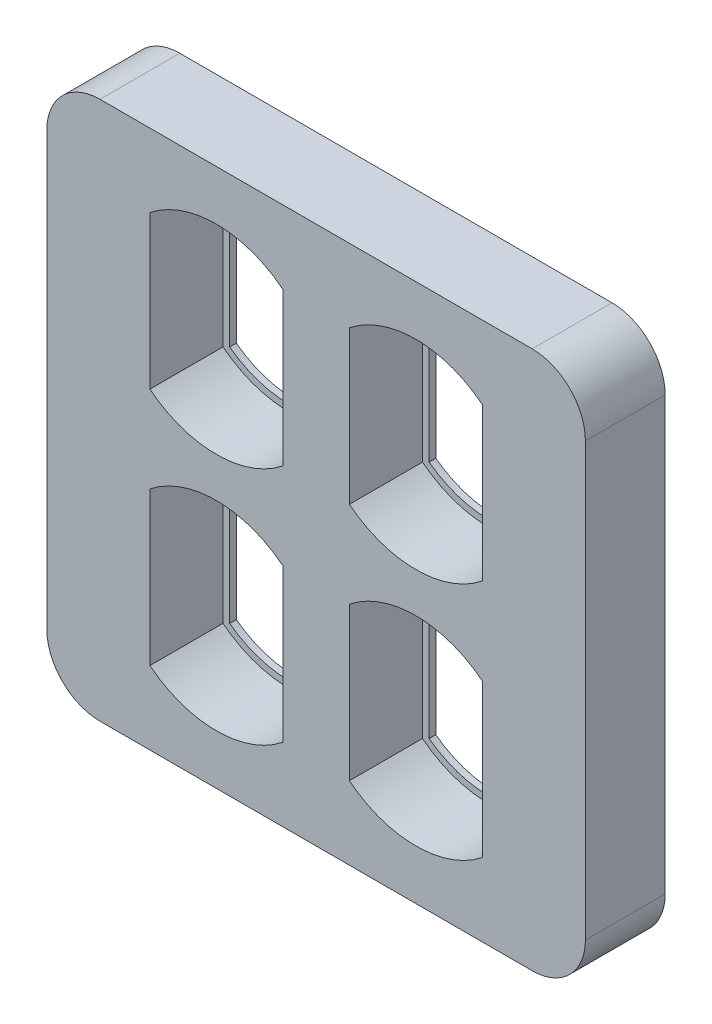
SolidWorks part; units mm, degrees
material "ABS-White"
ref_plane "Front Plane" through (0, 0, 0) normal (0, 0, 1) x (1, 0, 0)
ref_plane "Top Plane" through (0, 0, 0) normal (0, 1, 0) x (1, 0, 0)
ref_plane "Right Plane" through (0, 0, 0) normal (1, 0, 0) x (0, 0, -1)
sketch "Sketch1" plane through (0, 0, 0) normal (0, 0, 1) x (1, 0, 0)
  line L1 (-40.5, -40.5) -> (40.5, -40.5)
  line L2 (-40.5, -40.5) -> (-40.5, 40.5)
  line L3 (-40.5, 40.5) -> (40.5, 40.5)
  line L4 (40.5, -40.5) -> (40.5, 40.5)
  line L5 (-40.5, -40.5) -> (40.5, 40.5) construction
  line L6 (-40.5, 40.5) -> (40.5, -40.5) construction
  point P0 (0, 0)
  dimension "D1" = 81
  dimension "D2" = 81
extrude "Boss-Extrude1" add sketch "Sketch1" along normal blind 12
sketch "Sketch2" plane through (0, 0, 12) normal (0, 0, 1) x (1, 0, 0)
  line L0 (-15, 33) -> (-15, 3) construction
  line L2 (-25, 6.5) -> (-25, 29.5)
  line L4 (-5, 6.5) -> (-5, 29.5)
  line L5 (-25, 6.5) -> (-5, 29.5) construction
  line L6 (-25, 29.5) -> (-5, 6.5) construction
  arc A0 (-25, 29.5) -> (-5, 29.5) centre (-15, 16.9643) cw
  arc A1 (-25, 6.5) -> (-5, 6.5) centre (-15, 19.0357) ccw
  point P0 (-15, 18)
  dimension "D5" = 30
  dimension "D1" = 15
  dimension "D2" = 18
  dimension "D3" = 23
  dimension "D4" = 20
extrude "Cut-Extrude1" cut sketch "Sketch2" against normal offset from surface (11 mm away) 1 up to face at (0, 0, 0)
sketch "Sketch4" plane through (0, 0, 1) normal (0, 0, 1) x (1, 0, 0)
  line L4 (-6, 6.9911) -> (-6, 29.0089)
  line L5 (-24, 29.0089) -> (-24, 6.9911)
  line L6 (-6, 6.9911) -> (-6, 29.0089)
  line L7 (-24, 29.0089) -> (-24, 6.9911)
  arc A4 (-24, 6.9911) -> (-6, 6.9911) centre (-15, 19.0357) ccw
  arc A5 (-6, 29.0089) -> (-24, 29.0089) centre (-15, 16.9643) ccw
  arc A6 (-24, 6.9911) -> (-6, 6.9911) centre (-15, 19.0357) ccw
  arc A7 (-6, 29.0089) -> (-24, 29.0089) centre (-15, 16.9643) ccw
  dimension "D1" = 1
extrude "Cut-Extrude2" cut sketch "Sketch4" against normal through all
mirror "Mirror2" about plane through (0, 0, 0) normal (0, 1, 0) of "Cut-Extrude2", "Cut-Extrude1"
mirror "Mirror3" about plane through (0, 0, 0) normal (1, 0, 0) of "Mirror2", "Cut-Extrude1", "Cut-Extrude2"
fillet "Fillet1" radius 8 4 edges at (40.5, -40.5, 6) (-40.5, -40.5, 6) (40.5, 40.5, 6) (-40.5, 40.5, 6)
sketch "Sketch5" plane through (0, 0, 12) normal (0, 0, 1) x (1, 0, 0)
  line L0 (-40.5, 32.5) -> (-40.5, -32.5) construction
  line L1 (-32.5, -40.5) -> (32.5, -40.5) construction
  line L2 (40.5, -32.5) -> (40.5, 32.5) construction
  line L3 (32.5, 40.5) -> (-32.5, 40.5) construction
  line L4 (-40.5, 32.5) -> (-40.5, -32.5)
  line L5 (-32.5, -40.5) -> (32.5, -40.5)
  line L6 (40.5, -32.5) -> (40.5, 32.5)
  line L7 (32.5, 40.5) -> (-32.5, 40.5)
  arc A0 (-40.5, -32.5) -> (-32.5, -40.5) centre (-32.5, -32.5) ccw construction
  arc A1 (32.5, -40.5) -> (40.5, -32.5) centre (32.5, -32.5) ccw construction
  arc A2 (40.5, 32.5) -> (32.5, 40.5) centre (32.5, 32.5) ccw construction
  arc A3 (-32.5, 40.5) -> (-40.5, 32.5) centre (-32.5, 32.5) ccw construction
  arc A4 (-40.5, -32.5) -> (-32.5, -40.5) centre (-32.5, -32.5) ccw
  arc A5 (32.5, -40.5) -> (40.5, -32.5) centre (32.5, -32.5) ccw
  arc A6 (40.5, 32.5) -> (32.5, 40.5) centre (32.5, 32.5) ccw
  arc A7 (-32.5, 40.5) -> (-40.5, 32.5) centre (-32.5, 32.5) ccw
extrude "Extrude-Thin1" [suppressed] add sketch "Sketch5" along normal blind 17 thin
